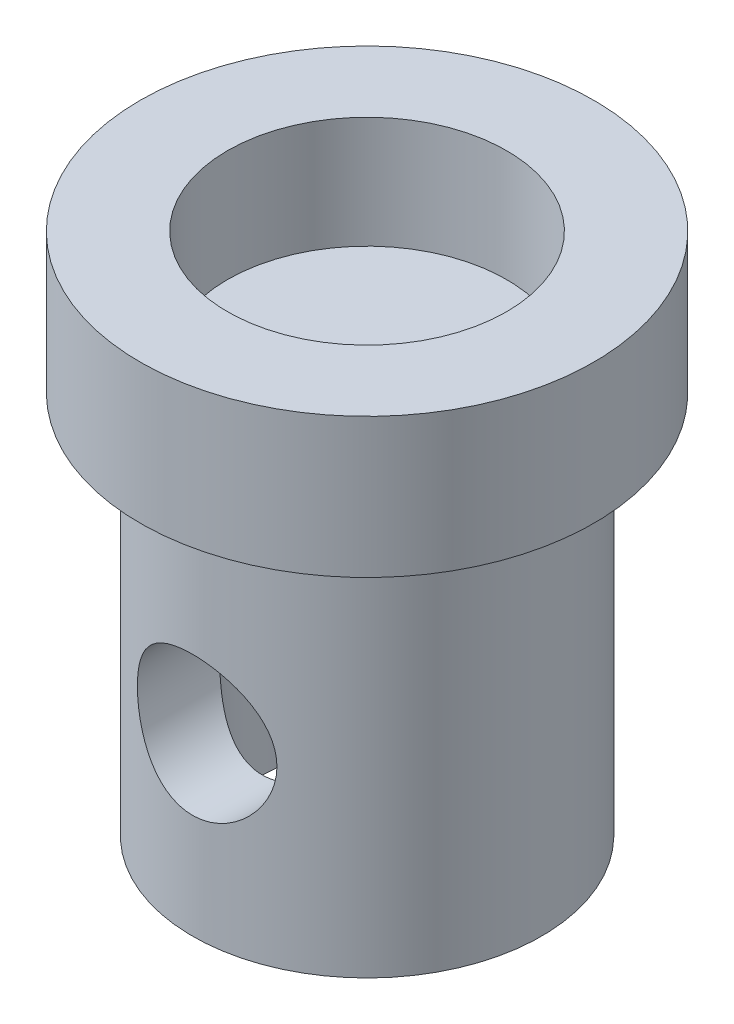
SolidWorks part; units mm, degrees
material "POM 乙缩醛共聚物"
ref_plane "前视基准面" through (0, 0, 0) normal (0, 0, 1) x (1, 0, 0)
ref_plane "上视基准面" through (0, 0, 0) normal (0, 1, 0) x (1, 0, 0)
ref_plane "右视基准面" through (0, 0, 0) normal (1, 0, 0) x (0, 0, -1)
sketch "草图1" plane through (0, 0, 0) normal (0, 0, 1) x (1, 0, 0)
  line L1 (6.5, 11) -> (6.5, 15)
  line L2 (6.5, 15) -> (4, 15)
  line L3 (4, 15) -> (4, 11.8)
  line L4 (4, 11.8) -> (0, 11.8)
  line L5 (0, 11.8) -> (0, 10.3)
  line L8 (6.5, 11) -> (6, 11)
  line L9 (5, 10) -> (5, 0)
  line L10 (5, 0) -> (3, 0)
  line L11 (0, 10.3) -> (3, 10.3)
  line L12 (3, 10.3) -> (3, 0)
  arc A0 (5, 10) -> (6, 11) centre (6, 10) cw
  point P8 (5.25, 15)
  dimension "D9" = 1
  dimension "D1" = 3.2
  dimension "D2" = 3
  dimension "D3" = 6.5
  dimension "D4" = 15
  dimension "D5" = 4
  dimension "D6" = 5
  dimension "D7" = 4
  dimension "D8" = 1.5
revolve "旋转1" add sketch "草图1" angle 360 about L5
sketch "草图2" plane through (0, 0, 0) normal (0, 0, 1) x (1, 0, 0)
  line L0 (0, 0) -> (0, 15) construction
  line L1 (4, 15) -> (-4, 15) construction
  line L7 (-5, 0) -> (5, 0) construction
  circle A0 centre (0, 5) radius 2
  dimension "D1" = 4
  dimension "D2" = 5
extrude "切除-拉伸1" cut sketch "草图2" against normal through all both and the other way through all
